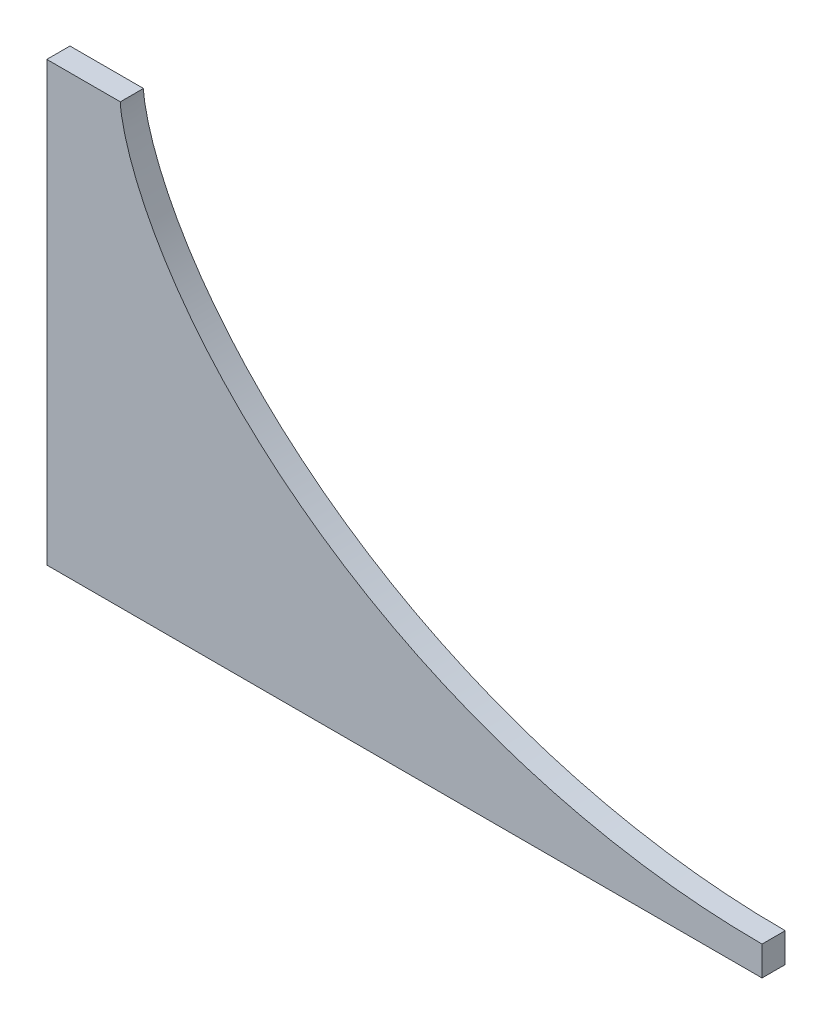
SolidWorks part; units mm, degrees
material "Oak"
ref_plane "Front Plane" through (0, 0, 0) normal (0, 0, 1) x (1, 0, 0)
ref_plane "Top Plane" through (0, 0, 0) normal (0, 1, 0) x (1, 0, 0)
ref_plane "Right Plane" through (0, 0, 0) normal (1, 0, 0) x (0, 0, -1)
sketch "Sketch1" plane through (0, 0, 0) normal (0, 0, 1) x (1, 0, 0)
  line L0 (-138.6064, 88.2396) -> (-154.4814, 88.2396)
  line L1 (-154.4814, 88.2396) -> (-154.4814, -6.35)
  line L2 (-154.4814, -6.35) -> (0, -6.35)
  line L3 (0, -6.35) -> (0, 0)
  spline S0 degree 4 poles (-138.6064, 88.2396) (-138.6064, 88.2065) (-138.6049, 88.1343) (-138.5978, 87.982) (-138.5845, 87.768) (-138.5634, 87.5118) (-138.5143, 87.0234) (-138.4252, 86.3366) (-138.2627, 85.3402) (-137.9978, 84.039) (-137.5439, 82.1639) (-136.7091, 79.3328) (-135.3815, 75.6924) (-133.4271, 71.3116) (-130.9787, 66.686) (-128.2488, 62.2009) (-125.2784, 57.8718) (-121.923, 53.476) (-117.4999, 48.2548) (-111.8465, 42.3725) (-104.8067, 36.0327) (-96.4812, 29.6258) (-87.7118, 23.8431) (-78.5622, 18.6846) (-69.0882, 14.1503) (-59.3407, 10.2402) (-49.3653, 6.9542) (-41.1115, 4.7916) (-34.6941, 3.4205) (-30.1777, 2.5974) (-27.5868, 2.166) (-24.3494, 1.6756) (-20.4356, 1.165) (-15.8882, 0.6832) (-11.2784, 0.3379) (-7.392, 0.1395) (-4.3526, 0.0486) (-2.4771, 0.0124) (-0.6178, -0.0003) (0.366, -0.001) (1.7, 0.0063) (2.7346, 0.0201) (3.8728, 0.0408) (4.9554, 0.0684) (6.0693, 0.1028) (7.1654, 0.1442) (8.546, 0.2045) (10.1961, 0.2907) (12.1241, 0.4113) (14.0479, 0.5561) (15.697, 0.6974) (16.7946, 0.8008) (17.3438, 0.8548) (17.618, 0.8824) knots 0 0 0 0 0 0.000751 0.001501 0.003003 0.004504 0.006005 0.011633 0.01726 0.025308 0.033355 0.051378 0.078048 0.105081 0.132113 0.159146 0.186178 0.213211 0.246016 0.300081 0.354147 0.408212 0.462277 0.516343 0.570408 0.624473 0.678538 0.732604 0.74612 0.759636 0.773152 0.786669 0.813701 0.840734 0.867767 0.881283 0.894799 0.901946 0.909093 0.914775 0.920456 0.926138 0.93182 0.937501 0.943183 0.948865 0.954546 0.96591 0.977273 0.988637 0.994318 1 1 1 1 1 construction
  spline S1 degree 4 poles (-138.6064, 88.2396) (-138.6064, 88.2065) (-138.6049, 88.1343) (-138.5978, 87.982) (-138.5845, 87.768) (-138.5634, 87.5118) (-138.5143, 87.0234) (-138.4252, 86.3366) (-138.2627, 85.3402) (-137.9978, 84.039) (-137.5439, 82.1639) (-136.7091, 79.3328) (-135.3815, 75.6924) (-133.4271, 71.3116) (-130.9787, 66.686) (-128.2488, 62.2009) (-125.2784, 57.8718) (-121.923, 53.476) (-117.4999, 48.2548) (-111.8465, 42.3725) (-104.8067, 36.0327) (-96.4812, 29.6258) (-87.7118, 23.8431) (-78.5622, 18.6846) (-69.0882, 14.1503) (-59.3407, 10.2402) (-49.3653, 6.9542) (-41.1115, 4.7916) (-34.6941, 3.4205) (-30.1777, 2.5974) (-27.5868, 2.166) (-24.3494, 1.6756) (-20.4356, 1.165) (-15.8882, 0.6832) (-11.2784, 0.3379) (-7.392, 0.1395) (-4.3526, 0.0486) (-2.4771, 0.0124) (-0.9332, 0.0018) (-0.3153, 0) (0, 0) knots 0 0 0 0 0 0.000751 0.001501 0.003003 0.004504 0.006005 0.011633 0.01726 0.025308 0.033355 0.051378 0.078048 0.105081 0.132113 0.159146 0.186178 0.213211 0.246016 0.300081 0.354147 0.408212 0.462277 0.516343 0.570408 0.624473 0.678538 0.732604 0.74612 0.759636 0.773152 0.786669 0.813701 0.840734 0.867767 0.881283 0.894799 0.901946 0.909093 0.909093 0.909093 0.909093 0.909093
  dimension "D1" = 138.6064
  dimension "D2" = 6.35
  dimension "D3" = 15.875
extrude "Boss-Extrude1" add sketch "Sketch1" along normal mid plane 5
